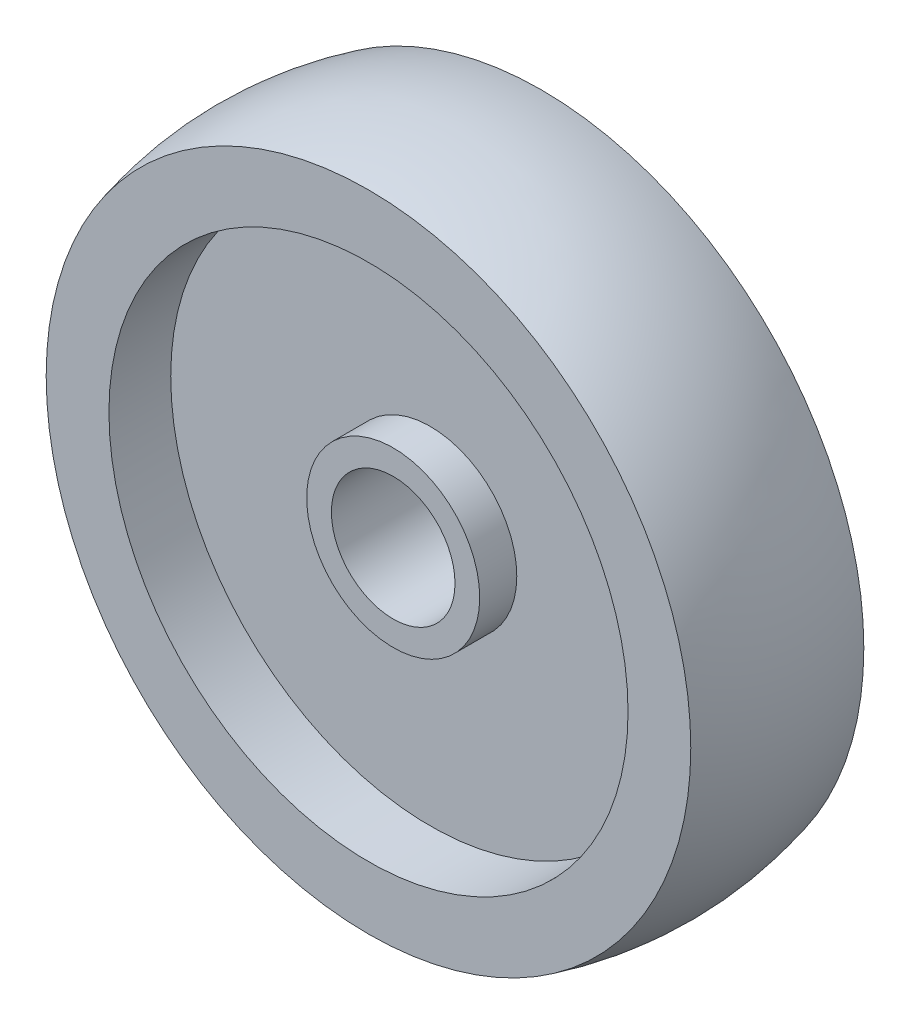
SolidWorks part; units mm, degrees
ref_plane "前视基准面" through (0, 0, 0) normal (0, 0, 1) x (1, 0, 0)
ref_plane "上视基准面" through (0, 0, 0) normal (0, 1, 0) x (1, 0, 0)
ref_plane "右视基准面" through (0, 0, 0) normal (1, 0, 0) x (0, 0, -1)
sketch "草图1" plane through (0, 0, 0) normal (0, 0, 1) x (1, 0, 0)
  circle A0 centre (0, 0) radius 5
  circle A1 centre (0, 0) radius 27
  dimension "D1" = 10
  dimension "D2" = 54
extrude "凸台-拉伸1" add sketch "草图1" along normal mid plane 14
sketch "草图2" plane through (0, 0, 0) normal (1, 0, 0) x (0, 0, -1)
  line L0 (7, 27) -> (-7, 27) construction
  line L1 (-7, 27) -> (7, 27)
  line L2 (7, 27) -> (7, 0)
  line L3 (7, -27) -> (7, 27) construction
  line L4 (7, 0) -> (-7, 0)
  line L5 (-7, 27) -> (-7, -27) construction
  line L6 (-7, 0) -> (-7, 27)
  circle A0 centre (0, 0) radius 27
revolve "切除-旋转1" cut sketch "草图2" angle 360 about L4
sketch "草图4" plane through (0, 0, 7) normal (0, 0, 1) x (1, 0, 0)
  circle A0 centre (0, 0) radius 21
  dimension "D1" = 42
extrude "切除-拉伸1" cut sketch "草图4" against normal blind 2
sketch "草图5" plane through (0, 0, 5) normal (0, 0, 1) x (1, 0, 0)
  circle A0 centre (0, 0) radius 21
  circle A1 centre (0, 0) radius 7
  dimension "D1" = 14
  dimension "D2" = 42
extrude "切除-拉伸2" cut sketch "草图5" against normal blind 3
mirror "镜向1" about plane through (0, 0, 0) normal (0, 0, 1) of "切除-拉伸2", "切除-拉伸1"
